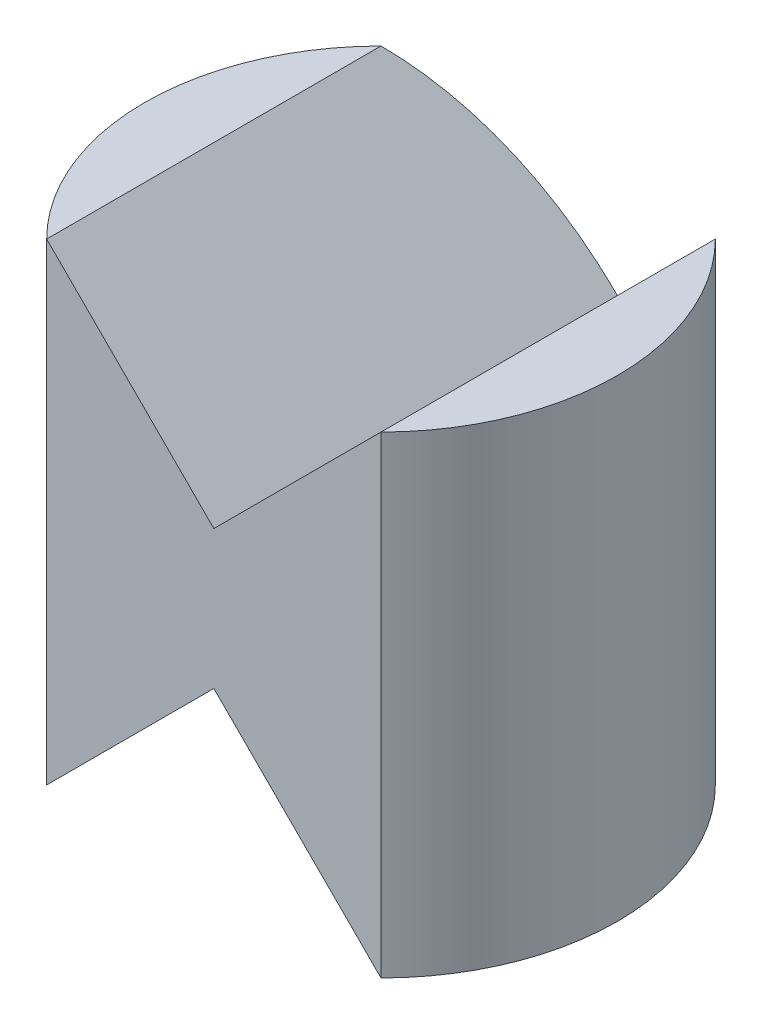
SolidWorks part; units mm, degrees
ref_plane "Front Plane" through (0, 0, 0) normal (0, 0, 1) x (1, 0, 0)
ref_plane "Top Plane" through (0, 0, 0) normal (0, 1, 0) x (1, 0, 0)
ref_plane "Right Plane" through (0, 0, 0) normal (1, 0, 0) x (0, 0, -1)
sketch "Sketch1" plane through (0, 0, 0) normal (0, 1, 0) x (1, 0, 0)
  line L0 (-1.7678, -1.7678) -> (1.7678, -1.7678)
  line L1 (-1.7678, -1.7678) -> (0, 0) construction
  line L2 (0, 0) -> (1.7678, -1.7678) construction
  arc A0 (-1.7678, -1.7678) -> (1.7678, -1.7678) centre (0, 0) cw
  dimension "D1" = 2.5
extrude "Boss-Extrude1" add sketch "Sketch1" along normal blind 5
sketch "Sketch2" plane through (0, 0, 1.7678) normal (0, 0, 1) x (1, 0, 0)
  line L0 (-1.7678, 0) -> (0, 1.7678)
  line L1 (0, 1.7678) -> (1.7678, 0)
  line L2 (-1.7678, 5) -> (0, 3.2322)
  line L3 (0, 3.2322) -> (1.7678, 5)
  line L4 (1.7678, 5) -> (-1.7678, 5)
  line L5 (-1.7678, 0) -> (1.7678, 0)
extrude "Cut-Extrude1" cut sketch "Sketch2" against normal up to next
